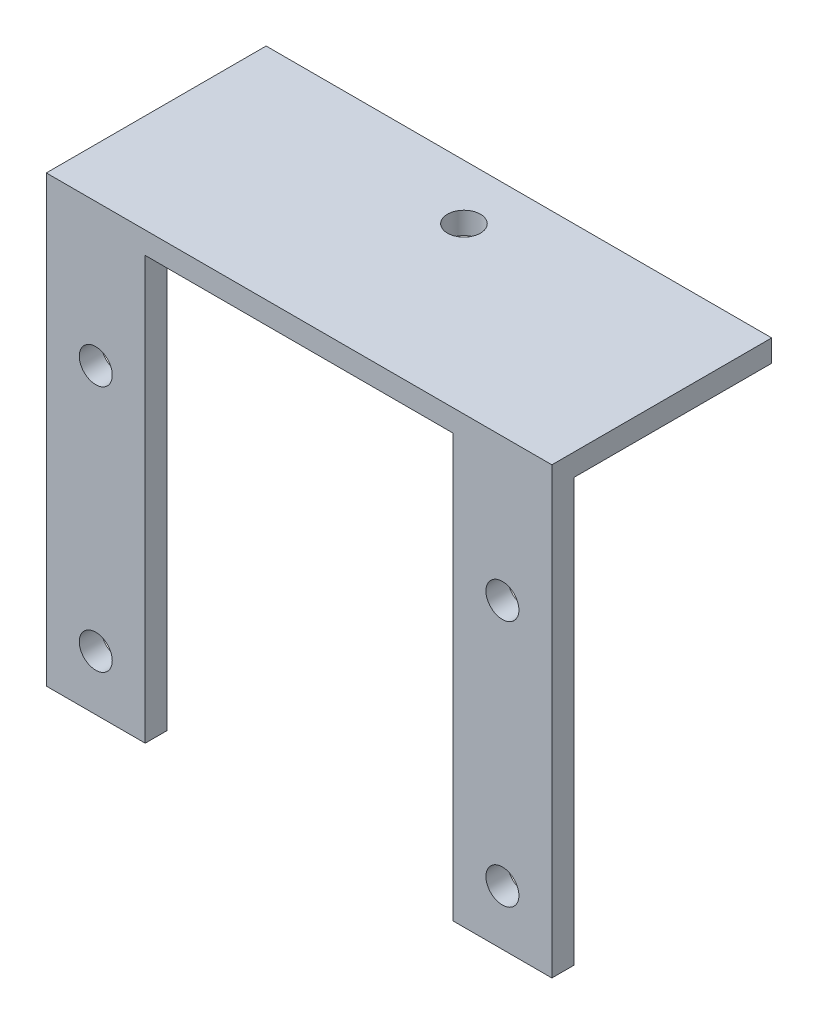
SolidWorks part; units mm, degrees
ref_plane "Front Plane" through (0, 0, 0) normal (0, 0, 1) x (1, 0, 0)
ref_plane "Top Plane" through (0, 0, 0) normal (0, 1, 0) x (1, 0, 0)
ref_plane "Right Plane" through (0, 0, 0) normal (1, 0, 0) x (0, 0, -1)
ref_plane "Plane1" through (0, 0, 0) normal (0, 0, 1) x (1, 0, 0)
ref_plane "Plane2" through (0, 4, 0) normal (0, 1, 0) x (1, 0, 0)
ref_plane "Plane3" through (0, 0, 0) normal (1, 0, 0) x (0, 0, -1)
sketch "Sketch3" plane through (0, 0, 0) normal (0, 0, 1) x (1, 0, 0)
  line L1 (-16.5158, -34.4383) -> (-25.5158, -34.4383)
  line L2 (-16.5158, -34.4383) -> (-16.5158, 5.5617)
  line L3 (-16.5158, 5.5617) -> (-25.5158, 5.5617)
  line L4 (-25.5158, -34.4383) -> (-25.5158, 5.5617)
  line L5 (20.4842, -34.4383) -> (11.4842, -34.4383)
  line L6 (20.4842, -34.4383) -> (20.4842, 5.5617)
  line L7 (20.4842, 5.5617) -> (11.4842, 5.5617)
  line L8 (11.4842, -34.4383) -> (11.4842, 5.5617)
  circle A0 centre (15.9842, -29.4383) radius 1.5
  circle A1 centre (-21.0158, -29.4383) radius 1.5
  circle A2 centre (-21.0158, -6.9383) radius 1.5
  circle A3 centre (15.9842, -6.9383) radius 1.5
  dimension "D4" = 3
  dimension "D5" = 4.5
  dimension "D6" = 5
  dimension "D7" = 22.5
  dimension "D8" = 22.5
  dimension "D9" = 5
  dimension "D1" = 40
  dimension "D2" = 9
  dimension "D3" = 46
  dimension "4.5" = 4.5
  dimension "D10" = 37
extrude "Boss-Extrude5" add sketch "Sketch3" along normal blind 2
sketch "Sketch5" plane through (0, 4, 0) normal (0, 1, 0) x (1, 0, 0)
  line L1 (-25.5158, -2) -> (20.4842, -2)
  line L2 (-25.5158, -2) -> (-25.5158, 18)
  line L3 (-25.5158, 18) -> (20.4842, 18)
  line L4 (20.4842, -2) -> (20.4842, 18)
  circle A0 centre (-2.5158, 13) radius 1.5
  point P7 (0, 0)
  point P9 (20.4842, 11.7243)
  dimension "D3" = 3
  dimension "D1" = 46
  dimension "D2" = 20
  dimension "D4" = 5
  dimension "D5" = 23
extrude "Boss-Extrude7" add sketch "Sketch5" along normal blind 2
